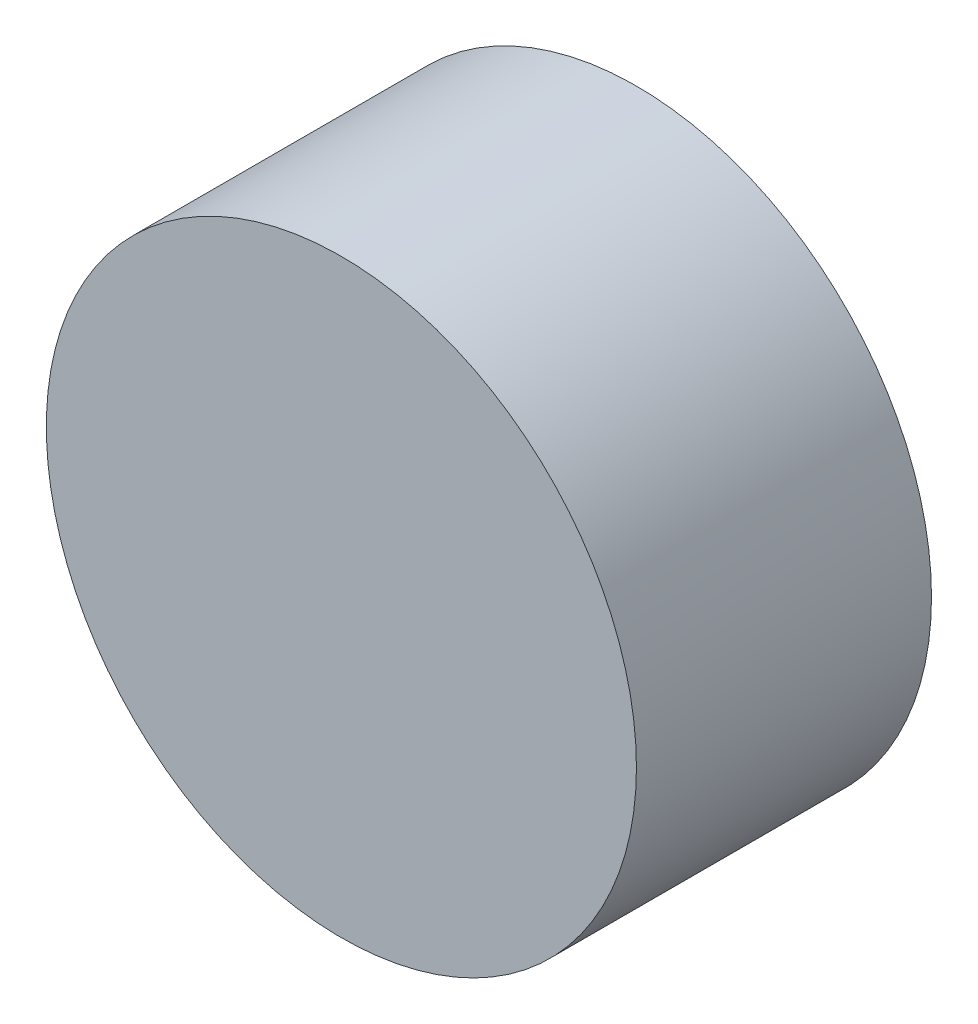
SolidWorks part; units mm, degrees
ref_plane "Front Plane" through (0, 0, 0) normal (0, 0, 1) x (1, 0, 0)
ref_plane "Top Plane" through (0, 0, 0) normal (0, 1, 0) x (1, 0, 0)
ref_plane "Right Plane" through (0, 0, 0) normal (1, 0, 0) x (0, 0, -1)
sketch "Sketch1" plane through (0, 0, 0) normal (0, 0, 1) x (1, 0, 0)
  circle A0 centre (0, 0) radius 10
  dimension "D1" = 20
extrude "Boss-Extrude1" add sketch "Sketch1" along normal blind 10
